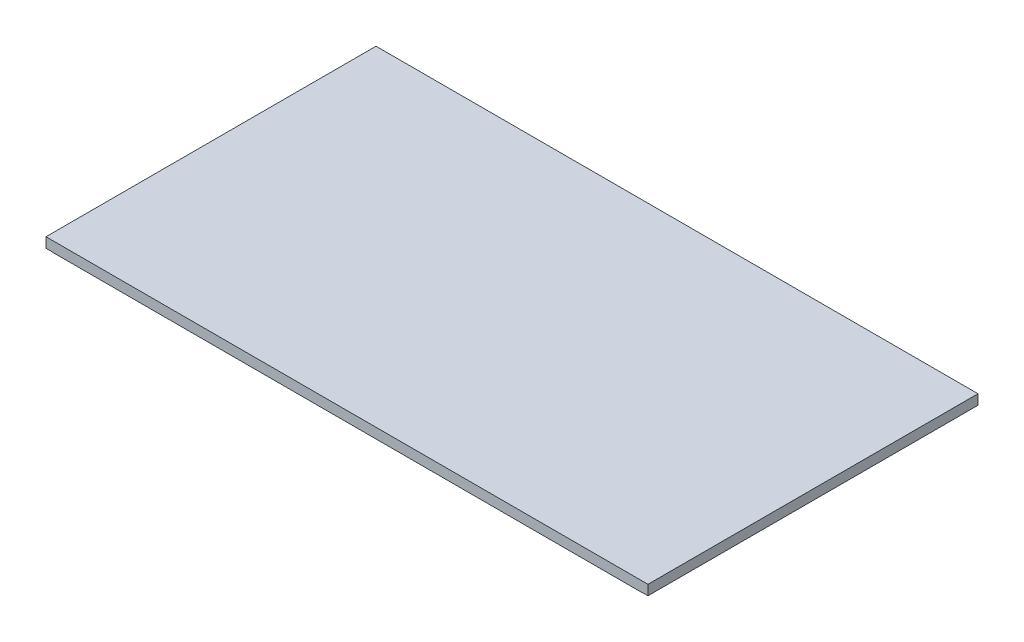
SolidWorks part; units mm, degrees
ref_plane "Front Plane" through (0, 0, 0) normal (0, 0, 1) x (1, 0, 0)
ref_plane "Top Plane" through (0, 0, 0) normal (0, 1, 0) x (1, 0, 0)
ref_plane "Right Plane" through (0, 0, 0) normal (1, 0, 0) x (0, 0, -1)
sketch "Sketch1" plane through (0, 0, 0) normal (0, 1, 0) x (1, 0, 0)
  line L0 (-58.25, 125) -> (58.25, 125)
  line L6 (-147.75, -125) -> (-147.75, 125) construction
  line L7 (-147.75, 125) -> (147.75, 125) construction
  line L8 (147.75, -125) -> (147.75, 125) construction
  line L9 (-147.75, -125) -> (147.75, 125) construction
  line L10 (-147.75, 125) -> (147.75, -125) construction
  line L11 (147.75, -81) -> (147.75, 81)
  line L12 (147.75, 81) -> (58.25, 81)
  line L13 (58.25, 81) -> (58.25, 125)
  line L14 (-15.8128, 0) -> (22.4682, 0) construction
  line L15 (0, 17.3156) -> (0, -20.1679) construction
  line L16 (-58.25, 81) -> (-58.25, 125)
  line L17 (-147.75, 81) -> (-58.25, 81)
  line L18 (-147.75, -81) -> (-147.75, 81)
  line L19 (-147.75, -125) -> (147.75, -125) construction
  line L20 (-147.75, -81) -> (-58.25, -81)
  line L21 (-58.25, -81) -> (-58.25, -125)
  line L22 (58.25, -81) -> (58.25, -125)
  line L23 (147.75, -81) -> (58.25, -81)
  line L24 (-58.25, -125) -> (58.25, -125)
  point P0 (0, 0)
  point P21 (0, 125)
  point P22 (-147.75, 0)
  point P27 (147.75, 0)
  dimension "D1" = 250
  dimension "D2" = 295.5
  dimension "D3" = 44
  dimension "D4" = 89.5
extrude "Boss-Extrude1" add sketch "Sketch1" along normal blind 5
sketch "Sketch2" plane through (0, 0, 0) normal (0, -1, 0) x (1, 0, 0)
  line L5 (-58.25, 81) -> (58.25, 81)
  line L13 (58.25, 81) -> (58.25, 125)
  line L14 (58.25, 125) -> (-58.25, 125)
  line L30 (-58.25, 125) -> (-58.25, 81)
  line L31 (-58.25, -81) -> (58.25, -81)
  line L32 (58.25, -81) -> (58.25, -125)
  line L33 (58.25, -125) -> (-58.25, -125)
  line L34 (-58.25, -125) -> (-58.25, -81) construction
  line L35 (-58.25, -125) -> (-58.25, -81)
extrude "Cut-Extrude1" cut sketch "Sketch2" against normal through all both and the other way through all
sketch "Sketch3" plane through (0, 0, 0) normal (0, -1, 0) x (1, 0, 0)
  line L0 (-147.75, -81) -> (-147.75, 81) construction
  line L1 (-150.75, 81) -> (-144.75, 81)
  line L2 (-150.75, 81) -> (-150.75, -81)
  line L3 (-150.75, -81) -> (-144.75, -81)
  line L4 (-144.75, 81) -> (-144.75, -81)
  line L5 (-150.75, 81) -> (-144.75, -81) construction
  line L6 (-150.75, -81) -> (-144.75, 81) construction
  line L7 (147.75, -81) -> (-147.75, -81) construction
  line L8 (147.75, 81) -> (147.75, -81) construction
  line L9 (144.75, 81) -> (150.75, 81)
  line L10 (144.75, 81) -> (144.75, -81)
  line L11 (144.75, -81) -> (150.75, -81)
  line L12 (150.75, 81) -> (150.75, -81)
  line L13 (144.75, 81) -> (150.75, -81) construction
  line L14 (144.75, -81) -> (150.75, 81) construction
  point P0 (-147.75, 0)
  point P9 (147.75, 0)
extrude "Cut-Extrude2" cut sketch "Sketch3" against normal blind 0.1
